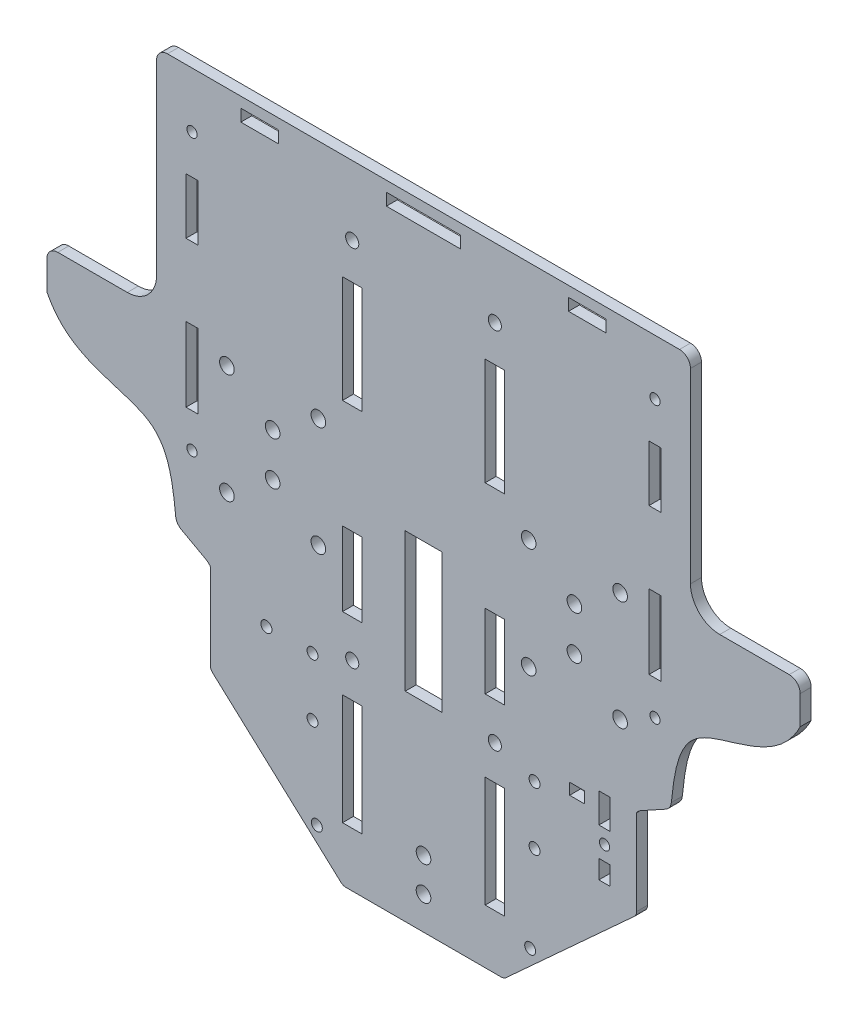
SolidWorks part; units mm, degrees
ref_plane "前视基准面" through (0, 0, 0) normal (0, 0, 1) x (1, 0, 0)
ref_plane "上视基准面" through (0, 0, 0) normal (0, 1, 0) x (1, 0, 0)
ref_plane "右视基准面" through (0, 0, 0) normal (1, 0, 0) x (0, 0, -1)
sketch "草图1" plane through (0, 0, 0) normal (0, 0, 1) x (1, 0, 0)
  line L24 (103, 13.6413) -> (103, 21.5)
  line L25 (100, 24.5) -> (81, 24.5)
  line L26 (73, 32.5) -> (73, 83.5)
  line L27 (70, 86.5) -> (-70, 86.5)
  line L28 (-73, 83.5) -> (-73, 32.5)
  line L29 (-81, 24.5) -> (-100, 24.5)
  line L30 (-103, 21.5) -> (-103, 13.6413)
  line L31 (-66.2261, -24.2572) -> (-59.3788, -28.0311)
  line L32 (-58.2905, -29.0565) -> (-22.0084, -86.5)
  line L33 (-22.0084, -86.5) -> (22.0084, -86.5)
  line L34 (22.0084, -86.5) -> (58.2905, -29.0565)
  line L35 (59.3788, -28.0311) -> (66.2261, -24.2572)
  line L52 (22, -21.5) -> (17, -21.5)
  line L53 (17, -1.5) -> (22, -1.5)
  line L54 (22, -1.5) -> (22, -21.5)
  line L55 (22, -71.5) -> (17, -71.5)
  line L56 (17, -71.5) -> (17, -41.5)
  line L57 (17, -41.5) -> (22, -41.5)
  line L58 (22, -41.5) -> (22, -71.5)
  line L59 (17, -21.5) -> (17, -1.5)
  line L60 (-10, 80.5) -> (-10, 83.5)
  line L61 (10, 83.5) -> (10, 80.5)
  line L62 (-10, 83.5) -> (10, 83.5)
  line L63 (10, 80.5) -> (-10, 80.5)
  line L64 (22, 28.5) -> (17, 28.5)
  line L65 (17, 58.5) -> (22, 58.5)
  line L66 (22, 58.5) -> (22, 28.5)
  line L67 (17, 28.5) -> (17, 58.5)
  line L68 (39.8, 80.5) -> (39.8, 83.5)
  line L69 (49.8, 80.5) -> (39.8, 80.5)
  line L70 (49.8, 83.5) -> (49.8, 80.5)
  line L71 (39.8, 83.5) -> (49.8, 83.5)
  line L72 (64.8, 45.5) -> (61.8, 45.5)
  line L73 (61.8, 45.5) -> (61.8, 60.5)
  line L74 (64.8, 60.5) -> (64.8, 45.5)
  line L75 (61.8, 60.5) -> (64.8, 60.5)
  line L76 (64.8, 5.5) -> (61.8, 5.5)
  line L77 (61.8, 5.5) -> (61.8, 25.5)
  line L78 (61.8, 25.5) -> (64.8, 25.5)
  line L79 (64.8, 25.5) -> (64.8, 5.5)
  line L83 (-17, -41.5) -> (-17, -71.5)
  line L85 (-22, -71.5) -> (-22, -41.5)
  line L87 (-17, -71.5) -> (-22, -71.5)
  line L89 (-22, -41.5) -> (-17, -41.5)
  line L91 (-17, -21.5) -> (-22, -21.5)
  line L93 (-17, -1.5) -> (-17, -21.5)
  line L95 (-22, -21.5) -> (-22, -1.5)
  line L97 (-22, -1.5) -> (-17, -1.5)
  line L99 (-22, 58.5) -> (-17, 58.5)
  line L101 (-17, 58.5) -> (-17, 28.5)
  line L103 (-22, 28.5) -> (-22, 58.5)
  line L105 (-17, 28.5) -> (-22, 28.5)
  line L107 (-61.8, 25.5) -> (-61.8, 5.5)
  line L109 (-64.8, 5.5) -> (-64.8, 25.5)
  line L111 (-64.8, 25.5) -> (-61.8, 25.5)
  line L113 (-61.8, 5.5) -> (-64.8, 5.5)
  line L115 (-64.8, 60.5) -> (-61.8, 60.5)
  line L117 (-61.8, 60.5) -> (-61.8, 45.5)
  line L119 (-61.8, 45.5) -> (-64.8, 45.5)
  line L121 (-64.8, 45.5) -> (-64.8, 60.5)
  line L123 (-49.8, 83.5) -> (-39.8, 83.5)
  line L125 (-39.8, 80.5) -> (-49.8, 80.5)
  line L127 (-39.8, 83.5) -> (-39.8, 80.5)
  line L129 (-49.8, 80.5) -> (-49.8, 83.5)
  circle A1 centre (63.3, -4.0699) radius 1.4
  circle A5 centre (30.3571, -51.4951) radius 1.5
  circle A6 centre (30.3571, -35.6308) radius 1.5
  circle A7 centre (63.3, 71.3731) radius 1.4
  circle A9 centre (0, -68.321) radius 2
  arc A20 (103, 21.5) -> (100, 24.5) centre (100, 21.5) ccw
  arc A21 (73, 32.5) -> (81, 24.5) centre (81, 32.5) ccw
  arc A22 (73, 83.5) -> (70, 86.5) centre (70, 83.5) ccw
  arc A23 (-70, 86.5) -> (-73, 83.5) centre (-70, 83.5) ccw
  arc A24 (-81, 24.5) -> (-73, 32.5) centre (-81, 32.5) ccw
  arc A25 (-100, 24.5) -> (-103, 21.5) centre (-100, 21.5) ccw
  arc A26 (-67.7618, -21.9409) -> (-66.2261, -24.2572) centre (-64.778, -21.6299) ccw
  arc A27 (-58.2905, -29.0565) -> (-59.3788, -28.0311) centre (-60.8269, -30.6585) ccw
  arc A28 (59.3788, -28.0311) -> (58.2905, -29.0565) centre (60.8269, -30.6585) ccw
  arc A29 (66.2261, -24.2572) -> (67.7618, -21.9409) centre (64.778, -21.6299) ccw
  circle A31 centre (-30.3571, -51.4951) radius 1.5
  circle A33 centre (-30.3571, -35.6308) radius 1.5
  circle A35 centre (-63.3, -4.0699) radius 1.4
  circle A37 centre (-63.3, 71.3731) radius 1.4
  spline S4 degree 3 poles (-103, 13.6413) (-99.0837, 5.8559) (-88.9592, 1.6503) (-69.9341, -3.2049) (-68.4607, -15.2368) (-67.7618, -21.9409) knots 0.024352 0.024352 0.024352 0.024352 0.394058 0.599531 0.911299 0.911299 0.911299 0.911299
  spline S5 degree 3 poles (67.7618, -21.9409) (68.4607, -15.2368) (69.9341, -3.2049) (88.9592, 1.6503) (99.0837, 5.8559) (103, 13.6413) knots 0.024352 0.024352 0.024352 0.024352 0.33612 0.541593 0.911299 0.911299 0.911299 0.911299
extrude "凸台-拉伸1" add sketch "草图1" along normal blind 3
sketch "草图2" plane through (0, 58.5, 0) normal (0, -1, 0) x (1, 0, 0)
  line L4 (-22, 0) -> (-17, 0)
  line L5 (-17, 0) -> (-17, 3)
  line L6 (-17, 3) -> (-22, 3)
  line L7 (-22, 3) -> (-22, 0)
  line L8 (-22, 0) -> (-17, 0)
  line L9 (-17, 0) -> (-17, 3)
  line L10 (-17, 3) -> (-22, 3)
  line L11 (-22, 3) -> (-22, 0)
  line L12 (17, 0) -> (22, 0)
  line L13 (22, 0) -> (22, 3)
  line L14 (22, 3) -> (17, 3)
  line L15 (17, 3) -> (17, 0)
  line L16 (17, 0) -> (22, 0)
  line L17 (22, 0) -> (22, 3)
  line L18 (22, 3) -> (17, 3)
  line L19 (17, 3) -> (17, 0)
  dimension "D1" = 0
  dimension "D2" = 0
extrude "凸台-拉伸2" add sketch "草图2" along normal blind 6
extrude "切除-拉伸1" cut sketch "草图3" against normal blind 3 contours A1 | A0 | A2 | A3
sketch "草图3" plane through (43.6924, 66.9039, 0) normal (0, 0, -1) x (-1, 0, 0)
  line L1 (21.6924, -1.1166) -> (26.6924, -1.1166)
  line L3 (21.6924, 2.4834) -> (26.6924, 2.4834)
  line L5 (60.6924, -1.1166) -> (65.6924, -1.1166)
  line L7 (60.6924, 2.4834) -> (65.6924, 2.4834)
  line L9 (21.6924, -100.6074) -> (26.6924, -100.6074)
  line L11 (21.6924, -97.0074) -> (26.6924, -97.0074)
  line L13 (60.6924, -97.0074) -> (65.6924, -97.0074)
  line L15 (60.6924, -100.6074) -> (65.6924, -100.6074)
  line L16 (65.6924, -100.6074) -> (64.6531, -99.8591)
  line L17 (26.6924, -100.6074) -> (25.6531, -99.8591)
  line L18 (26.6924, -1.1166) -> (25.6531, -0.3683)
  line L19 (65.6924, -1.1166) -> (64.6531, -0.3683)
  line L20 (61.7316, 1.7352) -> (60.6924, 2.4834)
  line L21 (22.7316, 1.7352) -> (21.6924, 2.4834)
  line L22 (61.7316, -97.7556) -> (60.6924, -97.0074)
  line L23 (22.7316, -97.7556) -> (21.6924, -97.0074)
  circle A0 centre (63.1924, -98.8074) radius 1.8
  circle A1 centre (24.1924, -98.8074) radius 1.8
  circle A2 centre (24.1924, 0.6834) radius 1.8
  circle A3 centre (63.1924, 0.6834) radius 1.8
sketch "草图4" plane through (0, 0, 3) normal (0, 0, 1) x (1, 0, 0)
  line L1 (-48.9148, 43.6984) -> (-33.6017, 43.6984)
  line L5 (-33.6017, -2.1865) -> (-41.2583, 15.6788)
  line L6 (-48.9148, -2.1865) -> (-41.2583, 15.6788)
  line L7 (-33.6017, 43.6984) -> (-41.2583, 25.8331)
  line L8 (-48.9148, -2.1865) -> (-33.6017, -2.1865)
  line L10 (-48.9148, 43.6984) -> (-41.2583, 25.8331)
  line L14 (-33.4258, 33.9546) -> (-39.0824, 20.7559)
  line L16 (-33.4258, 33.9546) -> (-33.4258, 7.5573)
  line L27 (-43.4342, 20.7559) -> (-49.0908, 7.5573)
  line L29 (-39.0824, 20.7559) -> (-33.4258, 7.5573)
  line L35 (-49.0908, 33.9546) -> (-49.0908, 7.5573)
  line L36 (-49.0908, 33.9546) -> (-43.4342, 20.7559)
extrude "切除-拉伸2" cut sketch "草图4" against normal blind 10
fillet "圆角1" radius 3 8 edges at (-33.6017, -2.1865, 1.5) (-48.9148, -2.1865, 1.5) (-41.2583, 15.6788, 1.5) (-43.4342, 20.7559, 1.5) (-39.0824, 20.7559, 1.5) (-41.2583, 25.8331, 1.5) (-48.9148, 43.6984, 1.5) (-33.6017, 43.6984, 1.5)
fillet "圆角2" radius 1 4 edges at (-33.4258, 7.5573, 1.5) (-33.4258, 33.9546, 1.5) (-49.0908, 7.5573, 1.5) (-49.0908, 33.9546, 1.5)
ref_plane "基准面1" through (0, 0, 0) normal (-1, 0, 0) x (0, 0, 1)
mirror "镜向1" about plane through (0, 0, 0) normal (-1, 0, 0) of "圆角1", "圆角2", "切除-拉伸2"
sketch "草图5" plane through (0, 52.5, 0) normal (0, -1, 0) x (1, 0, 0)
  line L4 (-22, 3) -> (-22, 0)
  line L5 (-22, 0) -> (-17, 0)
  line L6 (-17, 0) -> (-17, 3)
  line L7 (-17, 3) -> (-22, 3)
  line L8 (-22, 3) -> (-22, 0)
  line L9 (-22, 0) -> (-17, 0)
  line L10 (-17, 0) -> (-17, 3)
  line L11 (-17, 3) -> (-22, 3)
  line L12 (17, 3) -> (17, 0)
  line L13 (17, 0) -> (22, 0)
  line L14 (22, 0) -> (22, 3)
  line L15 (22, 3) -> (17, 3)
  line L16 (17, 3) -> (17, 0)
  line L17 (17, 0) -> (22, 0)
  line L18 (22, 0) -> (22, 3)
  line L19 (22, 3) -> (17, 3)
  dimension "D1" = 0
  dimension "D2" = 0
extrude "切除-拉伸3" cut sketch "草图5" against normal blind 5
ref_plane "基准面2" through (0, 0, 0) normal (-1, 0, 0) x (0, 0, 1)
extrude "切除-拉伸4" cut sketch "草图6" against normal blind 10
sketch "草图6" plane through (133.9432, -13.8725, 0) normal (0, 0, -1) x (-1, 0, 0)
  line L6 (126.9432, -16.0604) -> (140.9432, -16.0604)
  line L7 (126.9432, -16.0604) -> (126.9432, 27.9396)
  line L8 (126.9432, 27.9396) -> (140.9432, 27.9396)
  line L9 (140.9432, -16.0604) -> (140.9432, 27.9396)
  point P4 (133.9432, 5.9396)
sketch "草图7" plane through (0, 0, 3) normal (0, 0, 1) x (1, 0, 0)
  circle A3 centre (-53.7583, -9.2441) radius 2
  circle A4 centre (-28.7583, -9.2441) radius 2
  circle A5 centre (-53.7583, 20.7559) radius 2
  circle A6 centre (-28.7583, 20.7559) radius 2
  point P8 (-41.2583, 20.7559)
extrude "切除-拉伸7" cut sketch "草图7" against normal blind 10
mirror "镜向3" about plane through (0, 0, 0) normal (-1, 0, 0) of "切除-拉伸7"
sketch "草图8" plane through (0, 0, 3) normal (0, 0, 1) x (1, 0, 0)
  line L0 (7, 14.0671) -> (-7, 14.0671) construction
  line L1 (7, 14.0671) -> (-7, 14.0671)
  line L2 (7, -29.9329) -> (7, 14.0671) construction
  line L3 (7, -29.9329) -> (7, 14.0671)
  line L4 (-7, 14.0671) -> (-7, -29.9329) construction
  line L5 (-7, 14.0671) -> (-7, -29.9329)
  line L6 (-7, -29.9329) -> (7, -29.9329) construction
  line L7 (-7, -29.9329) -> (7, -29.9329)
  line L8 (-4, 11.0671) -> (-4, -26.9329)
  line L9 (-4, -26.9329) -> (4, -26.9329)
  line L10 (4, -26.9329) -> (4, 11.0671)
  line L11 (4, 11.0671) -> (-4, 11.0671)
  dimension "D1" = 3
extrude "凸台-拉伸3" add sketch "草图8" against normal up to surface (3 mm away) up to face at (30.7583, 20.7559, 0)
sketch "草图10" plane through (0, 0, 0) normal (0, 0, -1) x (-1, 0, 0)
  line L0 (4, 11.0671) -> (-4, 11.0671) construction
  line L1 (4, 11.0671) -> (-4, 11.0671)
sketch "草图11" plane through (4, 0, 0) normal (-1, 0, 0) x (0, 0, 1)
  line L4 (3, 11.0671) -> (0, 11.0671)
  line L5 (0, 11.0671) -> (0, -26.9329)
  line L6 (0, -26.9329) -> (3, -26.9329)
  line L7 (3, -26.9329) -> (3, 11.0671)
  line L8 (3, 11.0671) -> (0, 11.0671)
  line L9 (0, 11.0671) -> (0, -26.9329)
  line L10 (0, -26.9329) -> (3, -26.9329)
  line L11 (3, -26.9329) -> (3, 11.0671)
  dimension "D1" = 0
extrude "切除-拉伸8" cut sketch "草图11" against normal blind 1
sketch "草图12" plane through (-4, 0, 0) normal (1, 0, 0) x (0, 0, -1)
  line L4 (-3, -26.9329) -> (0, -26.9329)
  line L5 (0, -26.9329) -> (0, 11.0671)
  line L6 (0, 11.0671) -> (-3, 11.0671)
  line L7 (-3, 11.0671) -> (-3, -26.9329)
  line L8 (-3, -26.9329) -> (0, -26.9329)
  line L9 (0, -26.9329) -> (0, 11.0671)
  line L10 (0, 11.0671) -> (-3, 11.0671)
  line L11 (-3, 11.0671) -> (-3, -26.9329)
  dimension "D1" = 0
extrude "切除-拉伸9" cut sketch "草图12" against normal blind 1
sketch "草图14" plane through (0, 11.0671, 0) normal (0, -1, 0) x (1, 0, 0)
  line L4 (5, 3) -> (-5, 3)
  line L5 (-5, 3) -> (-5, 0)
  line L6 (-5, 0) -> (5, 0)
  line L7 (5, 0) -> (5, 3)
  line L8 (5, 3) -> (-5, 3)
  line L9 (-5, 3) -> (-5, 0)
  line L10 (-5, 0) -> (5, 0)
  line L11 (5, 0) -> (5, 3)
  dimension "D1" = 0
extrude "凸台-拉伸4" add sketch "草图14" along normal blind 5
sketch "草图15" plane through (0, -26.9329, 0) normal (0, 1, 0) x (1, 0, 0)
  line L4 (-5, -3) -> (5, -3)
  line L5 (5, -3) -> (5, 0)
  line L6 (5, 0) -> (-5, 0)
  line L7 (-5, 0) -> (-5, -3)
  line L8 (-5, -3) -> (5, -3)
  line L9 (5, -3) -> (5, 0)
  line L10 (5, 0) -> (-5, 0)
  line L11 (-5, 0) -> (-5, -3)
  dimension "D1" = 0
extrude "切除-拉伸10" cut sketch "草图15" against normal blind 5
sketch "草图16" plane through (0, 0, 0) normal (0, 0, -1) x (-1, 0, 0)
  line L0 (58.2905, -29.0565) -> (22.0084, -86.5) construction
  line L1 (58.2905, -29.0565) -> (22.0084, -86.5)
  line L2 (22.0084, -86.5) -> (58.2905, -86.5)
  line L3 (58.2905, -86.5) -> (58.2905, -29.0565)
  line L4 (-22.0084, -86.5) -> (-58.2905, -29.0565) construction
  line L5 (-22.0084, -86.5) -> (-58.2905, -29.0565)
  line L6 (-58.2905, -29.0565) -> (-58.2905, -86.5)
  line L7 (-58.2905, -86.5) -> (-22.0084, -86.5)
extrude "凸台-拉伸5" add sketch "草图16" against normal up to surface (3 mm away) up to face at (0, -12.9329, 3)
extrude "切除-拉伸11" cut sketch "草图17" against normal blind 10 contours L3 L5 L1
sketch "草图17" plane through (133.9432, -13.8725, 0) normal (0, 0, -1) x (-1, 0, 0)
  line L1 (192.2475, -39.4591) -> (155.9432, -72.6275)
  line L3 (192.2336, -72.6275) -> (155.9432, -72.6275)
  line L5 (192.2336, -72.6275) -> (192.2336, -39.4717)
mirror "镜向4" about plane through (0, 0, 0) normal (-1, 0, 0) of "切除-拉伸11"
extrude "切除-拉伸12" cut sketch "草图18" against normal blind 10
sketch "草图18" plane through (133.9432, -13.8725, 0) normal (0, 0, -1) x (-1, 0, 0)
  circle A1 centre (164.3003, -21.7583) radius 1.5
  circle A2 centre (176.8979, -21.7583) radius 1.5
extrude "切除-拉伸13" cut sketch "草图19" against normal blind 10
sketch "草图19" plane through (133.9432, -13.8725, 0) normal (0, 0, -1) x (-1, 0, 0)
  circle A1 centre (163.1127, -61.8608) radius 1.5
mirror "镜向5" about plane through (0, 0, 0) normal (-1, 0, 0) of "切除-拉伸13", "切除-拉伸12"
fillet "圆角3" radius 2 4 edges at (58.2905, -53.3442, 1.5) (22, -86.5, 1.5) (-22, -86.5, 1.5) (-58.2905, -53.3442, 1.5)
sketch "草图22" plane through (0, 0, 3) normal (0, 0, 1) x (1, 0, 0)
  line L1 (-21.2239, -86.5) -> (21.2239, -86.5) construction
  circle A2 centre (0, -77.5) radius 2
  dimension "D1" = 9
extrude "切除-拉伸14" cut sketch "草图22" against normal blind 10
sketch "草图23" plane through (0, 0, 3) normal (0, 0, 1) x (1, 0, 0)
  line L0 (-38.1513, 43.6984) -> (-44.3652, 43.6984) construction
  line L1 (-38.1513, 43.6984) -> (-44.3652, 43.6984)
  line L2 (-38.5009, 32.2671) -> (-35.3939, 39.5167) construction
  line L3 (-38.5009, 32.2671) -> (-35.3939, 39.5167)
  line L4 (-47.1227, 39.5167) -> (-44.0157, 32.2671) construction
  line L5 (-47.1227, 39.5167) -> (-44.0157, 32.2671)
  line L6 (-43.9407, 21.9377) -> (-47.1716, 29.4766) construction
  line L7 (-43.9407, 21.9377) -> (-47.1716, 29.4766)
  line L8 (-49.0908, 29.0827) -> (-49.0908, 12.4292) construction
  line L9 (-49.0908, 29.0827) -> (-49.0908, 12.4292)
  line L10 (-47.1716, 12.0353) -> (-43.9407, 19.5742) construction
  line L11 (-47.1716, 12.0353) -> (-43.9407, 19.5742)
  line L12 (-35.3449, 29.4766) -> (-38.5759, 21.9377) construction
  line L13 (-35.3449, 29.4766) -> (-38.5759, 21.9377)
  line L14 (-38.5759, 19.5742) -> (-35.3449, 12.0353) construction
  line L15 (-38.5759, 19.5742) -> (-35.3449, 12.0353)
  line L16 (-33.4258, 12.4292) -> (-33.4258, 29.0827) construction
  line L17 (-33.4258, 12.4292) -> (-33.4258, 29.0827)
  line L18 (-35.3939, 1.9952) -> (-38.5009, 9.2447) construction
  line L19 (-35.3939, 1.9952) -> (-38.5009, 9.2447)
  line L20 (-44.0157, 9.2447) -> (-47.1227, 1.9952) construction
  line L21 (-44.0157, 9.2447) -> (-47.1227, 1.9952)
  line L22 (-44.3652, -2.1865) -> (-38.1513, -2.1865) construction
  line L23 (-44.3652, -2.1865) -> (-38.1513, -2.1865)
  arc A0 (-44.3652, 43.6984) -> (-47.1227, 39.5167) centre (-44.3652, 40.6984) ccw construction
  arc A1 (-44.3652, 43.6984) -> (-47.1227, 39.5167) centre (-44.3652, 40.6984) ccw
  arc A2 (-35.3939, 39.5167) -> (-38.1513, 43.6984) centre (-38.1513, 40.6984) ccw construction
  arc A3 (-35.3939, 39.5167) -> (-38.1513, 43.6984) centre (-38.1513, 40.6984) ccw
  arc A4 (-44.0157, 32.2671) -> (-38.5009, 32.2671) centre (-41.2583, 33.4489) ccw construction
  arc A5 (-44.0157, 32.2671) -> (-38.5009, 32.2671) centre (-41.2583, 33.4489) ccw
  arc A6 (-47.1716, 29.4766) -> (-49.0908, 29.0827) centre (-48.0908, 29.0827) ccw construction
  arc A7 (-47.1716, 29.4766) -> (-49.0908, 29.0827) centre (-48.0908, 29.0827) ccw
  arc A8 (-49.0908, 12.4292) -> (-47.1716, 12.0353) centre (-48.0908, 12.4292) ccw construction
  arc A9 (-49.0908, 12.4292) -> (-47.1716, 12.0353) centre (-48.0908, 12.4292) ccw
  arc A10 (-43.9407, 19.5742) -> (-43.9407, 21.9377) centre (-46.6981, 20.7559) ccw construction
  arc A11 (-43.9407, 19.5742) -> (-43.9407, 21.9377) centre (-46.6981, 20.7559) ccw
  arc A12 (-38.5759, 21.9377) -> (-38.5759, 19.5742) centre (-35.8184, 20.7559) ccw construction
  arc A13 (-38.5759, 21.9377) -> (-38.5759, 19.5742) centre (-35.8184, 20.7559) ccw
  arc A14 (-35.3449, 12.0353) -> (-33.4258, 12.4292) centre (-34.4258, 12.4292) ccw construction
  arc A15 (-35.3449, 12.0353) -> (-33.4258, 12.4292) centre (-34.4258, 12.4292) ccw
  arc A16 (-33.4258, 29.0827) -> (-35.3449, 29.4766) centre (-34.4258, 29.0827) ccw construction
  arc A17 (-33.4258, 29.0827) -> (-35.3449, 29.4766) centre (-34.4258, 29.0827) ccw
  arc A18 (-38.5009, 9.2447) -> (-44.0157, 9.2447) centre (-41.2583, 8.063) ccw construction
  arc A19 (-38.5009, 9.2447) -> (-44.0157, 9.2447) centre (-41.2583, 8.063) ccw
  arc A20 (-47.1227, 1.9952) -> (-44.3652, -2.1865) centre (-44.3652, 0.8135) ccw construction
  arc A21 (-47.1227, 1.9952) -> (-44.3652, -2.1865) centre (-44.3652, 0.8135) ccw
  arc A22 (-38.1513, -2.1865) -> (-35.3939, 1.9952) centre (-38.1513, 0.8135) ccw construction
  arc A23 (-38.1513, -2.1865) -> (-35.3939, 1.9952) centre (-38.1513, 0.8135) ccw
extrude "凸台-拉伸6" add sketch "草图23" against normal up to surface (3 mm away)
ref_plane "基准面3" through (0, 0, 0) normal (-1, 0, 0) x (0, 0, 1)
mirror "镜向6" about plane through (0, 0, 0) normal (-1, 0, 0) of "凸台-拉伸6"
sketch "草图25" plane through (0, 0, 3) normal (0, 0, 1) x (1, 0, 0)
  line L0 (-22, 57.5) -> (-22, 28.5) construction
  line L1 (-22, 57.5) -> (-22, 28.5)
  line L2 (-17, 57.5) -> (-22, 57.5) construction
  line L3 (-17, 57.5) -> (-22, 57.5)
  line L4 (-17, 28.5) -> (-17, 57.5) construction
  line L5 (-17, 28.5) -> (-17, 57.5)
  line L6 (-22, 28.5) -> (-17, 28.5) construction
  line L7 (-22, 28.5) -> (-17, 28.5)
  line L8 (-17, -1.5) -> (-22, -1.5) construction
  line L9 (-17, -1.5) -> (-22, -1.5)
  line L10 (-17, -21.5) -> (-17, -1.5) construction
  line L11 (-17, -21.5) -> (-17, -1.5)
  line L12 (-22, -1.5) -> (-22, -21.5) construction
  line L13 (-22, -1.5) -> (-22, -21.5)
  line L14 (-22, -21.5) -> (-17, -21.5) construction
  line L15 (-22, -21.5) -> (-17, -21.5)
  line L16 (-17, -41.5) -> (-22, -41.5) construction
  line L17 (-17, -41.5) -> (-22, -41.5)
  line L18 (-22, -41.5) -> (-22, -71.5) construction
  line L19 (-22, -41.5) -> (-22, -71.5)
  line L20 (-17, -71.5) -> (-17, -41.5) construction
  line L21 (-17, -71.5) -> (-17, -41.5)
  line L22 (-22, -71.5) -> (-17, -71.5) construction
  line L23 (-22, -71.5) -> (-17, -71.5)
  line L24 (22, -41.5) -> (17, -41.5) construction
  line L25 (22, -41.5) -> (17, -41.5)
  line L26 (22, -71.5) -> (22, -41.5) construction
  line L27 (22, -71.5) -> (22, -41.5)
  line L28 (17, -71.5) -> (22, -71.5) construction
  line L29 (17, -71.5) -> (22, -71.5)
  line L30 (17, -41.5) -> (17, -71.5) construction
  line L31 (17, -41.5) -> (17, -71.5)
  line L32 (22, -1.5) -> (17, -1.5) construction
  line L33 (22, -1.5) -> (17, -1.5)
  line L34 (22, -21.5) -> (22, -1.5) construction
  line L35 (22, -21.5) -> (22, -1.5)
  line L36 (17, -1.5) -> (17, -21.5) construction
  line L37 (17, -1.5) -> (17, -21.5)
  line L38 (17, -21.5) -> (22, -21.5) construction
  line L39 (17, -21.5) -> (22, -21.5)
  line L40 (22, 57.5) -> (17, 57.5) construction
  line L41 (22, 57.5) -> (17, 57.5)
  line L42 (17, 57.5) -> (17, 28.5) construction
  line L43 (17, 57.5) -> (17, 28.5)
  line L44 (22, 28.5) -> (22, 57.5) construction
  line L45 (22, 28.5) -> (22, 57.5)
  line L46 (17, 28.5) -> (22, 28.5) construction
  line L47 (17, 28.5) -> (22, 28.5)
  line L48 (-64.8, 60.5) -> (-64.8, 45.5) construction
  line L49 (-64.8, 60.5) -> (-64.8, 45.5)
  line L50 (-61.8, 60.5) -> (-64.8, 60.5) construction
  line L51 (-61.8, 60.5) -> (-64.8, 60.5)
  line L52 (-61.8, 45.5) -> (-61.8, 60.5) construction
  line L53 (-61.8, 45.5) -> (-61.8, 60.5)
  line L54 (-64.8, 45.5) -> (-61.8, 45.5) construction
  line L55 (-64.8, 45.5) -> (-61.8, 45.5)
  line L56 (-61.8, 25.5) -> (-64.8, 25.5) construction
  line L57 (-61.8, 25.5) -> (-64.8, 25.5)
  line L58 (-64.8, 25.5) -> (-64.8, 5.5) construction
  line L59 (-64.8, 25.5) -> (-64.8, 5.5)
  line L60 (-61.8, 5.5) -> (-61.8, 25.5) construction
  line L61 (-61.8, 5.5) -> (-61.8, 25.5)
  line L62 (-64.8, 5.5) -> (-61.8, 5.5) construction
  line L63 (-64.8, 5.5) -> (-61.8, 5.5)
  line L64 (61.8, 60.5) -> (61.8, 45.5) construction
  line L65 (61.8, 60.5) -> (61.8, 45.5)
  line L66 (64.8, 60.5) -> (61.8, 60.5) construction
  line L67 (64.8, 60.5) -> (61.8, 60.5)
  line L68 (64.8, 45.5) -> (64.8, 60.5) construction
  line L69 (64.8, 45.5) -> (64.8, 60.5)
  line L70 (61.8, 45.5) -> (64.8, 45.5) construction
  line L71 (61.8, 45.5) -> (64.8, 45.5)
  line L72 (64.8, 25.5) -> (61.8, 25.5) construction
  line L73 (64.8, 25.5) -> (61.8, 25.5)
  line L74 (61.8, 25.5) -> (61.8, 5.5) construction
  line L75 (61.8, 25.5) -> (61.8, 5.5)
  line L76 (64.8, 5.5) -> (64.8, 25.5) construction
  line L77 (64.8, 5.5) -> (64.8, 25.5)
  line L78 (61.8, 5.5) -> (64.8, 5.5) construction
  line L79 (61.8, 5.5) -> (64.8, 5.5)
  line L80 (-64.9, 25.6) -> (-64.9, 5.4)
  line L81 (-64.9, 5.4) -> (-61.7, 5.4)
  line L82 (-61.7, 5.4) -> (-61.7, 25.6)
  line L83 (-61.7, 25.6) -> (-64.9, 25.6)
  line L84 (-64.9, 45.4) -> (-61.7, 45.4)
  line L85 (-61.7, 45.4) -> (-61.7, 60.6)
  line L86 (-61.7, 60.6) -> (-64.9, 60.6)
  line L87 (-64.9, 60.6) -> (-64.9, 45.4)
  line L88 (-22.1, -41.4) -> (-22.1, -71.6)
  line L89 (-22.1, -71.6) -> (-16.9, -71.6)
  line L90 (-16.9, -71.6) -> (-16.9, -41.4)
  line L91 (-16.9, -41.4) -> (-22.1, -41.4)
  line L92 (-22.1, -1.4) -> (-22.1, -21.6)
  line L93 (-22.1, -21.6) -> (-16.9, -21.6)
  line L94 (-16.9, -21.6) -> (-16.9, -1.4)
  line L95 (-16.9, -1.4) -> (-22.1, -1.4)
  line L96 (-22.1, 57.6) -> (-22.1, 28.4)
  line L97 (-22.1, 28.4) -> (-16.9, 28.4)
  line L98 (-16.9, 28.4) -> (-16.9, 57.6)
  line L99 (-16.9, 57.6) -> (-22.1, 57.6)
  line L100 (16.9, 57.6) -> (16.9, 28.4)
  line L101 (16.9, 28.4) -> (22.1, 28.4)
  line L102 (22.1, 28.4) -> (22.1, 57.6)
  line L103 (22.1, 57.6) -> (16.9, 57.6)
  line L104 (16.9, -1.4) -> (16.9, -21.6)
  line L105 (16.9, -21.6) -> (22.1, -21.6)
  line L106 (22.1, -21.6) -> (22.1, -1.4)
  line L107 (22.1, -1.4) -> (16.9, -1.4)
  line L108 (16.9, -41.4) -> (16.9, -71.6)
  line L109 (16.9, -71.6) -> (22.1, -71.6)
  line L110 (22.1, -71.6) -> (22.1, -41.4)
  line L111 (22.1, -41.4) -> (16.9, -41.4)
  line L112 (61.7, 60.6) -> (61.7, 45.4)
  line L113 (61.7, 45.4) -> (64.9, 45.4)
  line L114 (64.9, 45.4) -> (64.9, 60.6)
  line L115 (64.9, 60.6) -> (61.7, 60.6)
  line L116 (61.7, 25.6) -> (61.7, 5.4)
  line L117 (61.7, 5.4) -> (64.9, 5.4)
  line L118 (64.9, 5.4) -> (64.9, 25.6)
  line L119 (64.9, 25.6) -> (61.7, 25.6)
  dimension "D1" = 0.1
extrude "切除-拉伸15" cut sketch "草图25" against normal blind 10
sketch "草图26" plane through (0, 0, 3) normal (0, 0, 1) x (1, 0, 0)
  line L3 (-49.8, 80.5) -> (-39.8, 80.5) construction
  line L5 (-49.8, 80.5) -> (-39.8, 80.5)
  line L6 (-39.8, 83.5) -> (-49.8, 83.5) construction
  line L7 (-39.8, 83.5) -> (-49.8, 83.5)
  line L8 (-49.8, 83.5) -> (-49.8, 80.5) construction
  line L9 (-49.8, 83.5) -> (-49.8, 80.5)
  line L10 (-39.8, 80.5) -> (-39.8, 83.5) construction
  line L11 (-39.8, 80.5) -> (-39.8, 83.5)
  line L12 (10, 83.5) -> (-10, 83.5) construction
  line L13 (10, 83.5) -> (-10, 83.5)
  line L14 (-10, 83.5) -> (-10, 80.5) construction
  line L15 (-10, 83.5) -> (-10, 80.5)
  line L16 (-10, 80.5) -> (10, 80.5) construction
  line L17 (-10, 80.5) -> (10, 80.5)
  line L18 (10, 80.5) -> (10, 83.5) construction
  line L19 (10, 80.5) -> (10, 83.5)
  line L20 (49.8, 83.5) -> (39.8, 83.5) construction
  line L21 (49.8, 83.5) -> (39.8, 83.5)
  line L22 (39.8, 83.5) -> (39.8, 80.5) construction
  line L23 (39.8, 83.5) -> (39.8, 80.5)
  line L24 (39.8, 80.5) -> (49.8, 80.5) construction
  line L25 (39.8, 80.5) -> (49.8, 80.5)
  line L26 (49.8, 80.5) -> (49.8, 83.5) construction
  line L27 (49.8, 80.5) -> (49.8, 83.5)
  line L28 (49.95, 83.65) -> (39.65, 83.65)
  line L29 (39.65, 83.65) -> (39.65, 80.35)
  line L30 (39.65, 80.35) -> (49.95, 80.35)
  line L31 (49.95, 80.35) -> (49.95, 83.65)
  line L32 (-10.15, 80.35) -> (10.15, 80.35)
  line L33 (10.15, 80.35) -> (10.15, 83.65)
  line L34 (10.15, 83.65) -> (-10.15, 83.65)
  line L35 (-10.15, 83.65) -> (-10.15, 80.35)
  line L36 (-49.95, 80.35) -> (-39.65, 80.35)
  line L37 (-39.65, 80.35) -> (-39.65, 83.65)
  line L38 (-39.65, 83.65) -> (-49.95, 83.65)
  line L39 (-49.95, 83.65) -> (-49.95, 80.35)
  dimension "D1" = 0.15
extrude "切除-拉伸16" cut sketch "草图26" against normal blind 10
sketch "草图27" plane through (0, 0, 3) normal (0, 0, 1) x (1, 0, 0)
  line L0 (-61.7, 45.4) -> (-61.7, 60.6) construction
  line L1 (-61.7, 45.4) -> (-61.7, 60.6)
  line L2 (-61.7, 60.6) -> (-64.9, 60.6) construction
  line L3 (-61.7, 60.6) -> (-64.9, 60.6)
  line L4 (-64.9, 60.6) -> (-64.9, 45.4) construction
  line L5 (-64.9, 60.6) -> (-64.9, 45.4)
  line L6 (-64.9, 45.4) -> (-61.7, 45.4) construction
  line L7 (-64.9, 45.4) -> (-61.7, 45.4)
  line L8 (-61.7, 25.6) -> (-64.9, 25.6) construction
  line L9 (-61.7, 25.6) -> (-64.9, 25.6)
  line L10 (-64.9, 25.6) -> (-64.9, 5.4) construction
  line L11 (-64.9, 25.6) -> (-64.9, 5.4)
  line L12 (-61.7, 5.4) -> (-61.7, 25.6) construction
  line L13 (-61.7, 5.4) -> (-61.7, 25.6)
  line L14 (-64.9, 5.4) -> (-61.7, 5.4) construction
  line L15 (-64.9, 5.4) -> (-61.7, 5.4)
  line L16 (-16.9, -41.4) -> (-22.1, -41.4) construction
  line L17 (-16.9, -41.4) -> (-22.1, -41.4)
  line L18 (-22.1, -41.4) -> (-22.1, -71.6) construction
  line L19 (-22.1, -41.4) -> (-22.1, -71.6)
  line L20 (-16.9, -71.6) -> (-16.9, -41.4) construction
  line L21 (-16.9, -71.6) -> (-16.9, -41.4)
  line L22 (-22.1, -71.6) -> (-16.9, -71.6) construction
  line L23 (-22.1, -71.6) -> (-16.9, -71.6)
  line L24 (-16.9, -1.4) -> (-22.1, -1.4) construction
  line L25 (-16.9, -1.4) -> (-22.1, -1.4)
  line L26 (-22.1, -1.4) -> (-22.1, -21.6) construction
  line L27 (-22.1, -1.4) -> (-22.1, -21.6)
  line L28 (-16.9, -21.6) -> (-16.9, -1.4) construction
  line L29 (-16.9, -21.6) -> (-16.9, -1.4)
  line L30 (-22.1, -21.6) -> (-16.9, -21.6) construction
  line L31 (-22.1, -21.6) -> (-16.9, -21.6)
  line L32 (-16.9, 57.6) -> (-22.1, 57.6) construction
  line L33 (-16.9, 57.6) -> (-22.1, 57.6)
  line L34 (-22.1, 57.6) -> (-22.1, 28.4) construction
  line L35 (-22.1, 57.6) -> (-22.1, 28.4)
  line L36 (-16.9, 28.4) -> (-16.9, 57.6) construction
  line L37 (-16.9, 28.4) -> (-16.9, 57.6)
  line L38 (-22.1, 28.4) -> (-16.9, 28.4) construction
  line L39 (-22.1, 28.4) -> (-16.9, 28.4)
  line L40 (22.1, 57.6) -> (16.9, 57.6) construction
  line L41 (22.1, 57.6) -> (16.9, 57.6)
  line L42 (16.9, 57.6) -> (16.9, 28.4) construction
  line L43 (16.9, 57.6) -> (16.9, 28.4)
  line L44 (22.1, 28.4) -> (22.1, 57.6) construction
  line L45 (22.1, 28.4) -> (22.1, 57.6)
  line L46 (16.9, 28.4) -> (22.1, 28.4) construction
  line L47 (16.9, 28.4) -> (22.1, 28.4)
  line L48 (22.1, -1.4) -> (16.9, -1.4) construction
  line L49 (22.1, -1.4) -> (16.9, -1.4)
  line L50 (16.9, -1.4) -> (16.9, -21.6) construction
  line L51 (16.9, -1.4) -> (16.9, -21.6)
  line L52 (22.1, -21.6) -> (22.1, -1.4) construction
  line L53 (22.1, -21.6) -> (22.1, -1.4)
  line L54 (16.9, -21.6) -> (22.1, -21.6) construction
  line L55 (16.9, -21.6) -> (22.1, -21.6)
  line L56 (22.1, -41.4) -> (16.9, -41.4) construction
  line L57 (22.1, -41.4) -> (16.9, -41.4)
  line L58 (16.9, -41.4) -> (16.9, -71.6) construction
  line L59 (16.9, -41.4) -> (16.9, -71.6)
  line L60 (22.1, -71.6) -> (22.1, -41.4) construction
  line L61 (22.1, -71.6) -> (22.1, -41.4)
  line L62 (16.9, -71.6) -> (22.1, -71.6) construction
  line L63 (16.9, -71.6) -> (22.1, -71.6)
  line L64 (64.9, 60.6) -> (61.7, 60.6) construction
  line L65 (64.9, 60.6) -> (61.7, 60.6)
  line L66 (61.7, 60.6) -> (61.7, 45.4) construction
  line L67 (61.7, 60.6) -> (61.7, 45.4)
  line L68 (64.9, 45.4) -> (64.9, 60.6) construction
  line L69 (64.9, 45.4) -> (64.9, 60.6)
  line L70 (61.7, 45.4) -> (64.9, 45.4) construction
  line L71 (61.7, 45.4) -> (64.9, 45.4)
  line L72 (64.9, 25.6) -> (61.7, 25.6) construction
  line L73 (64.9, 25.6) -> (61.7, 25.6)
  line L74 (64.9, 5.4) -> (64.9, 25.6) construction
  line L75 (64.9, 5.4) -> (64.9, 25.6)
  line L76 (61.7, 25.6) -> (61.7, 5.4) construction
  line L77 (61.7, 25.6) -> (61.7, 5.4)
  line L78 (61.7, 5.4) -> (64.9, 5.4) construction
  line L79 (61.7, 5.4) -> (64.9, 5.4)
  line L80 (-64.95, 60.65) -> (-64.95, 45.35)
  line L81 (-64.95, 45.35) -> (-61.65, 45.35)
  line L82 (-61.65, 45.35) -> (-61.65, 60.65)
  line L83 (-61.65, 60.65) -> (-64.95, 60.65)
  line L84 (-64.95, 25.65) -> (-64.95, 5.35)
  line L85 (-64.95, 5.35) -> (-61.65, 5.35)
  line L86 (-61.65, 5.35) -> (-61.65, 25.65)
  line L87 (-61.65, 25.65) -> (-64.95, 25.65)
  line L88 (-22.15, 57.65) -> (-22.15, 28.35)
  line L89 (-22.15, 28.35) -> (-16.85, 28.35)
  line L90 (-16.85, 28.35) -> (-16.85, 57.65)
  line L91 (-16.85, 57.65) -> (-22.15, 57.65)
  line L92 (-22.15, -1.35) -> (-22.15, -21.65)
  line L93 (-22.15, -21.65) -> (-16.85, -21.65)
  line L94 (-16.85, -21.65) -> (-16.85, -1.35)
  line L95 (-16.85, -1.35) -> (-22.15, -1.35)
  line L96 (-22.15, -41.35) -> (-22.15, -71.65)
  line L97 (-22.15, -71.65) -> (-16.85, -71.65)
  line L98 (-16.85, -71.65) -> (-16.85, -41.35)
  line L99 (-16.85, -41.35) -> (-22.15, -41.35)
  line L100 (16.85, 57.65) -> (16.85, 28.35)
  line L101 (16.85, 28.35) -> (22.15, 28.35)
  line L102 (22.15, 28.35) -> (22.15, 57.65)
  line L103 (22.15, 57.65) -> (16.85, 57.65)
  line L104 (16.85, -1.35) -> (16.85, -21.65)
  line L105 (16.85, -21.65) -> (22.15, -21.65)
  line L106 (22.15, -21.65) -> (22.15, -1.35)
  line L107 (22.15, -1.35) -> (16.85, -1.35)
  line L108 (16.85, -41.35) -> (16.85, -71.65)
  line L109 (16.85, -71.65) -> (22.15, -71.65)
  line L110 (22.15, -71.65) -> (22.15, -41.35)
  line L111 (22.15, -41.35) -> (16.85, -41.35)
  line L112 (61.65, 60.65) -> (61.65, 45.35)
  line L113 (61.65, 45.35) -> (64.95, 45.35)
  line L114 (64.95, 45.35) -> (64.95, 60.65)
  line L115 (64.95, 60.65) -> (61.65, 60.65)
  line L116 (61.65, 25.65) -> (61.65, 5.35)
  line L117 (61.65, 5.35) -> (64.95, 5.35)
  line L118 (64.95, 5.35) -> (64.95, 25.65)
  line L119 (64.95, 25.65) -> (61.65, 25.65)
  dimension "D1" = 0.05
extrude "切除-拉伸17" cut sketch "草图27" against normal blind 10
extrude "切除-拉伸18" cut sketch "草图29" against normal blind 10
sketch "草图29" plane through (133.9432, -13.8725, 0) normal (0, 0, -1) x (-1, 0, 0)
  circle A1 centre (104.7736, -61.8608) radius 1.5
mirror "镜向7" about plane through (0, 0, 0) normal (-1, 0, 0) of "切除-拉伸18"
extrude "切除-拉伸19" cut sketch "草图30" against normal blind 10 contours L13 L14 L11 L12 | L9 L6 L2 L3
sketch "草图30" plane through (133.9432, -13.8725, 3) normal (0, 0, 1) x (1, 0, 0)
  line L2 (-85.9432, -23.2212) -> (-82.9432, -23.2212)
  line L3 (-82.9432, -23.2212) -> (-82.9432, -15.2212)
  line L6 (-85.9432, -15.2212) -> (-85.9432, -23.2212)
  line L8 (-85.9432, -23.2212) -> (-85.9432, -15.2212)
  line L9 (-85.9432, -15.2212) -> (-82.9432, -15.2212)
  line L11 (-82.9432, -31.2212) -> (-85.9432, -31.2212)
  line L12 (-85.9432, -31.2212) -> (-85.9432, -36.2212)
  line L13 (-85.9432, -36.2212) -> (-82.9432, -36.2212)
  line L14 (-82.9432, -36.2212) -> (-82.9432, -31.2212)
sketch "草图32" plane through (0, 0, 3) normal (0, 0, 1) x (1, 0, 0)
  circle A0 centre (42.9547, -35.6308) radius 1.5 construction
  circle A1 centre (42.9547, -35.6308) radius 1.5
extrude "凸台-拉伸7" add sketch "草图32" against normal up to surface (3 mm away)
extrude "切除-拉伸21" cut sketch "草图33" against normal blind 3
sketch "草图33" plane through (133.9432, -13.8725, 0) normal (0, 0, -1) x (-1, 0, 0)
  circle A0 centre (84.4432, -27.143) radius 1.4
extrude "切除-拉伸22" cut sketch "草图34" against normal blind 3
sketch "草图34" plane through (133.9432, -13.8725, 0) normal (0, 0, -1) x (-1, 0, 0)
  line L8 (93.9432, -20.1818) -> (93.9432, -17.1818)
  line L9 (93.9432, -17.1818) -> (89.9432, -17.1818)
  line L10 (89.9432, -17.1818) -> (89.9432, -20.1818)
  line L11 (89.9432, -20.1818) -> (93.9432, -20.1818)
sketch "草图35" plane through (0, 0, 3) normal (0, 0, 1) x (1, 0, 0)
  line L0 (44, -34.0543) -> (40, -34.0543) construction
  line L1 (44, -34.0543) -> (40, -34.0543)
  line L2 (40, -34.0543) -> (40, -31.0543) construction
  line L3 (40, -34.0543) -> (40, -31.0543)
  line L4 (40, -31.0543) -> (44, -31.0543) construction
  line L5 (40, -31.0543) -> (44, -31.0543)
  line L6 (44, -31.0543) -> (44, -34.0543) construction
  line L7 (44, -31.0543) -> (44, -34.0543)
  line L8 (48, -29.0937) -> (51, -29.0937) construction
  line L9 (48, -29.0937) -> (51, -29.0937)
  line L10 (48, -29.0937) -> (48, -37.0937) construction
  line L11 (48, -29.0937) -> (48, -37.0937)
  line L12 (51, -37.0937) -> (51, -29.0937) construction
  line L13 (51, -37.0937) -> (51, -29.0937)
  line L14 (48, -37.0937) -> (51, -37.0937) construction
  line L15 (48, -37.0937) -> (51, -37.0937)
  line L16 (51, -45.0937) -> (48, -45.0937) construction
  line L17 (51, -45.0937) -> (48, -45.0937)
  line L18 (48, -45.0937) -> (48, -50.0937) construction
  line L19 (48, -45.0937) -> (48, -50.0937)
  line L20 (48, -50.0937) -> (51, -50.0937) construction
  line L21 (48, -50.0937) -> (51, -50.0937)
  line L22 (51, -50.0937) -> (51, -45.0937) construction
  line L23 (51, -50.0937) -> (51, -45.0937)
  line L24 (47.95, -50.1437) -> (51.05, -50.1437)
  line L25 (51.05, -50.1437) -> (51.05, -45.0437)
  line L26 (51.05, -45.0437) -> (47.95, -45.0437)
  line L27 (47.95, -45.0437) -> (47.95, -50.1437)
  line L28 (47.95, -37.1437) -> (51.05, -37.1437)
  line L29 (51.05, -37.1437) -> (51.05, -29.0437)
  line L30 (47.95, -29.0437) -> (51.05, -29.0437)
  line L31 (47.95, -29.0437) -> (47.95, -37.1437)
  line L32 (44.05, -34.1043) -> (39.95, -34.1043)
  line L33 (39.95, -34.1043) -> (39.95, -31.0043)
  line L34 (39.95, -31.0043) -> (44.05, -31.0043)
  line L35 (44.05, -31.0043) -> (44.05, -34.1043)
  dimension "D1" = 0.05
extrude "切除-拉伸23" cut sketch "草图35" against normal blind 3
sketch "草图36" plane through (0, 0, 3) normal (0, 0, 1) x (1, 0, 0)
  circle A5 centre (-41.2583, 11.845) radius 2
  circle A6 centre (-41.2583, 0) radius 2
  circle A7 centre (41.2583, 0) radius 2
  circle A8 centre (41.2583, 11.845) radius 2
extrude "切除-拉伸24" cut sketch "草图36" against normal blind 10
